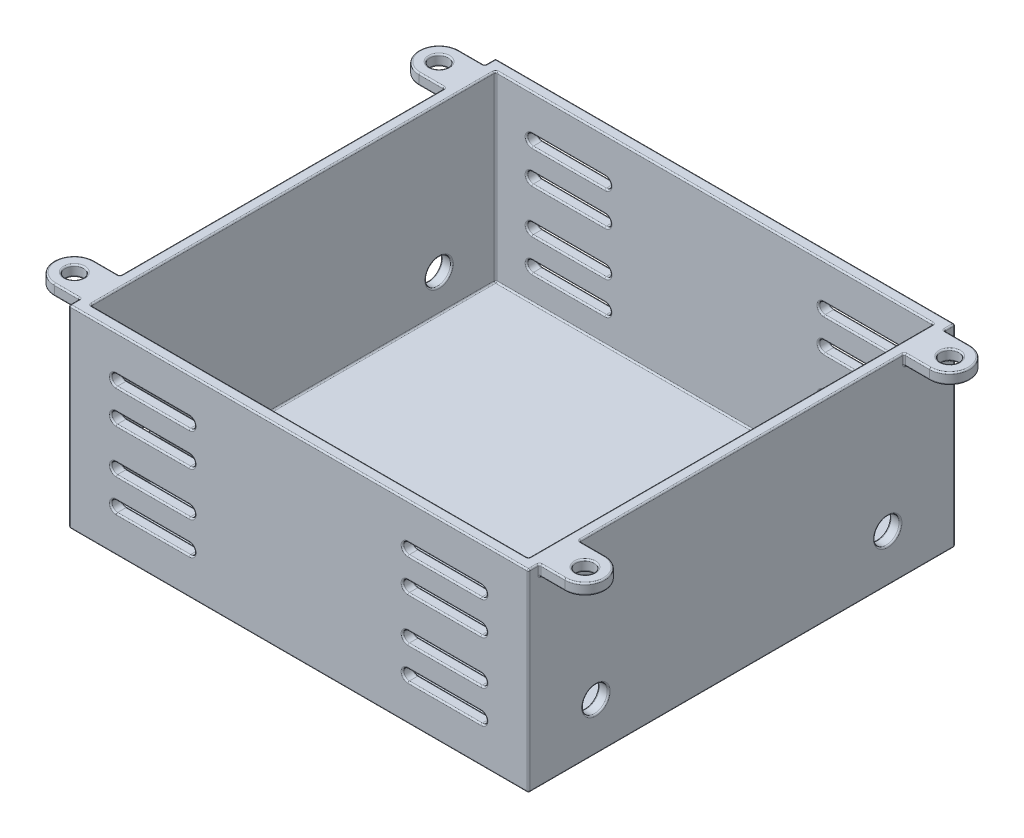
SolidWorks part; units mm, degrees
ref_plane "Front Plane" through (0, 0, 0) normal (0, 0, 1) x (1, 0, 0)
ref_plane "Top Plane" through (0, 0, 0) normal (0, 1, 0) x (1, 0, 0)
ref_plane "Right Plane" through (0, 0, 0) normal (1, 0, 0) x (0, 0, -1)
sketch "Sketch1" plane through (0, 0, 0) normal (0, 1, 0) x (1, 0, 0)
  line L0 (-35, 27.75) -> (35, 27.75) construction
  line L1 (-35, 25) -> (35, 25) construction
  line L2 (-35, 25) -> (-35, -25) construction
  line L3 (-35, -25) -> (35, -25) construction
  line L4 (35, 25) -> (35, -25) construction
  line L5 (-35, 25) -> (35, -25) construction
  line L6 (-35, -25) -> (35, 25) construction
  line L7 (-30, 27.75) -> (30, 27.75)
  line L8 (-35, -27.75) -> (35, -27.75) construction
  line L9 (30, 27.75) -> (30, -27.75)
  line L10 (30, -27.75) -> (-30, -27.75)
  line L11 (-30, -27.75) -> (-30, 27.75)
  line L12 (-35, 22.25) -> (-30, 22.25)
  line L13 (35, 22.25) -> (30, 22.25)
  line L14 (-35, -22.25) -> (-30, -22.25)
  line L15 (35, -22.25) -> (30, -22.25)
  circle A0 centre (-35, 25) radius 1.25
  circle A1 centre (-35, -25) radius 1.25
  circle A2 centre (35, -25) radius 1.25
  circle A3 centre (35, 25) radius 1.25
  circle A4 centre (-35, 25) radius 2.75
  circle A5 centre (35, 25) radius 2.75
  circle A6 centre (35, -25) radius 2.75
  circle A7 centre (-35, -25) radius 2.75
  point P0 (0, 0)
  dimension "D3" = 2.5
  dimension "D1" = 50
  dimension "D2" = 70
  dimension "D5" = 60
  dimension "D6" = 30
  dimension "D4" = 1.5
sketch "Sketch2" plane through (0, 0, 0) normal (0, 1, 0) x (1, 0, 0)
  line L0 (-30, -27.75) -> (-30, 27.75) construction
  line L1 (-30, -27.75) -> (-30, 27.75)
  line L2 (-30, 27.75) -> (30, 27.75) construction
  line L3 (-30, 27.75) -> (30, 27.75)
  line L4 (30, 27.75) -> (30, -27.75) construction
  line L5 (30, 27.75) -> (30, -27.75)
  line L6 (30, -27.75) -> (-30, -27.75) construction
  line L7 (30, -27.75) -> (-30, -27.75)
  line L8 (-31.5, -29.25) -> (-31.5, 29.25)
  line L9 (-31.5, 29.25) -> (31.5, 29.25)
  line L10 (31.5, 29.25) -> (31.5, -29.25)
  line L11 (31.5, -29.25) -> (-31.5, -29.25)
  dimension "D1" = 1.5
extrude "Boss-Extrude1" add sketch "Sketch2" against normal blind 25
sketch "Sketch3" plane through (0, -25, 0) normal (0, -1, 0) x (1, 0, 0)
  line L4 (31.5, 29.25) -> (-31.5, 29.25)
  line L5 (-31.5, 29.25) -> (-31.5, -29.25)
  line L6 (-31.5, -29.25) -> (31.5, -29.25)
  line L7 (31.5, -29.25) -> (31.5, 29.25)
  line L8 (31.5, 29.25) -> (-31.5, 29.25)
  line L9 (-31.5, 29.25) -> (-31.5, -29.25)
  line L10 (-31.5, -29.25) -> (31.5, -29.25)
  line L11 (31.5, -29.25) -> (31.5, 29.25)
  dimension "D1" = 0
extrude "Boss-Extrude2" add sketch "Sketch3" along normal blind 1.5
sketch "Sketch4" plane through (0, 0, 0) normal (0, 1, 0) x (1, 0, 0)
  line L0 (-35, 27.75) -> (35, 27.75) construction
  line L1 (-35, 27.75) -> (-30, 27.75)
  line L2 (-35, 22.25) -> (-30, 22.25) construction
  line L3 (-35, 22.25) -> (-30, 22.25)
  line L4 (35, 22.25) -> (30, 22.25) construction
  line L5 (35, 22.25) -> (30, 22.25)
  line L6 (-35, -22.25) -> (-30, -22.25) construction
  line L7 (-35, -27.75) -> (35, -27.75) construction
  line L8 (35, -22.25) -> (30, -22.25) construction
  line L9 (30, 27.75) -> (30, -27.75) construction
  line L10 (-30, -27.75) -> (-30, 27.75) construction
  line L11 (-35, -22.25) -> (-30, -22.25)
  line L12 (-35, -27.75) -> (-30, -27.75)
  line L13 (35, -22.25) -> (30, -22.25)
  line L14 (30, 27.75) -> (30, 22.25)
  line L15 (-30, -27.75) -> (-30, -22.25)
  line L16 (-30, 22.25) -> (-30, 27.75)
  line L17 (30, 27.75) -> (35, 27.75)
  line L18 (30, -22.25) -> (30, -27.75)
  line L19 (30, -27.75) -> (35, -27.75)
  circle A0 centre (-35, 25) radius 2.75 construction
  arc A1 (-35, 27.75) -> (-35, 22.25) centre (-35, 25) ccw
  circle A2 centre (-35, 25) radius 1.25 construction
  circle A3 centre (-35, 25) radius 1.25
  circle A4 centre (35, 25) radius 1.25 construction
  circle A5 centre (35, 25) radius 2.75 construction
  circle A6 centre (35, 25) radius 1.25
  arc A7 (35, 22.25) -> (35, 27.75) centre (35, 25) ccw
  circle A8 centre (-35, -25) radius 1.25 construction
  circle A9 centre (-35, -25) radius 2.75 construction
  circle A10 centre (35, -25) radius 1.25 construction
  circle A11 centre (35, -25) radius 2.75 construction
  circle A12 centre (-35, -25) radius 1.25
  arc A13 (-35, -22.25) -> (-35, -27.75) centre (-35, -25) ccw
  circle A14 centre (35, -25) radius 1.25
  arc A15 (35, -27.75) -> (35, -22.25) centre (35, -25) ccw
extrude "Boss-Extrude3" add sketch "Sketch4" against normal blind 1.5
sketch "Sketch5" plane through (0, 0, 0) normal (0, 0, 1) x (1, 0, 0)
  line L0 (-31.5, -13.25) -> (31.5, -13.25) construction
  line L1 (-31.5, -26.5) -> (-31.5, 0) construction
  line L2 (31.5, -26.5) -> (31.5, 0) construction
  line L3 (-25, -5.75) -> (-15, -5.75) construction
  line L4 (-25, -5) -> (-15, -5)
  line L5 (-25, -6.5) -> (-15, -6.5)
  line L6 (-25, -10.25) -> (-15, -10.25) construction
  line L7 (-25, -9.5) -> (-15, -9.5)
  line L8 (-25, -11) -> (-15, -11)
  line L9 (0, -13.25) -> (0, -21.5125) construction
  line L10 (-25, -16.25) -> (-15, -16.25) construction
  line L11 (-25, -17) -> (-15, -17)
  line L12 (-25, -15.5) -> (-15, -15.5)
  line L13 (-25, -20.75) -> (-15, -20.75) construction
  line L14 (-25, -21.5) -> (-15, -21.5)
  line L15 (-25, -20) -> (-15, -20)
  line L16 (25, -20.75) -> (15, -20.75) construction
  line L17 (25, -21.5) -> (15, -21.5)
  line L18 (25, -20) -> (15, -20)
  line L19 (25, -16.25) -> (15, -16.25) construction
  line L20 (25, -17) -> (15, -17)
  line L21 (25, -15.5) -> (15, -15.5)
  line L22 (25, -10.25) -> (15, -10.25) construction
  line L23 (25, -9.5) -> (15, -9.5)
  line L24 (25, -11) -> (15, -11)
  line L25 (25, -5.75) -> (15, -5.75) construction
  line L26 (25, -5) -> (15, -5)
  line L27 (25, -6.5) -> (15, -6.5)
  arc A0 (-25, -5) -> (-25, -6.5) centre (-25, -5.75) ccw
  arc A1 (-15, -6.5) -> (-15, -5) centre (-15, -5.75) ccw
  arc A2 (-25, -9.5) -> (-25, -11) centre (-25, -10.25) ccw
  arc A3 (-15, -11) -> (-15, -9.5) centre (-15, -10.25) ccw
  arc A4 (-25, -17) -> (-25, -15.5) centre (-25, -16.25) cw
  arc A5 (-15, -15.5) -> (-15, -17) centre (-15, -16.25) cw
  arc A6 (-25, -21.5) -> (-25, -20) centre (-25, -20.75) cw
  arc A7 (-15, -20) -> (-15, -21.5) centre (-15, -20.75) cw
  arc A8 (25, -21.5) -> (25, -20) centre (25, -20.75) ccw
  arc A9 (15, -20) -> (15, -21.5) centre (15, -20.75) ccw
  arc A10 (25, -17) -> (25, -15.5) centre (25, -16.25) ccw
  arc A11 (15, -15.5) -> (15, -17) centre (15, -16.25) ccw
  arc A12 (25, -9.5) -> (25, -11) centre (25, -10.25) cw
  arc A13 (15, -11) -> (15, -9.5) centre (15, -10.25) cw
  arc A14 (25, -5) -> (25, -6.5) centre (25, -5.75) cw
  arc A15 (15, -6.5) -> (15, -5) centre (15, -5.75) cw
  point P8 (-20, -5.75)
  point P16 (-20, -10.25)
  point P25 (-20, -16.25)
  point P32 (-20, -20.75)
  point P39 (20, -20.75)
  point P46 (20, -16.25)
  point P53 (20, -10.25)
  point P60 (20, -5.75)
  dimension "D1" = 10
  dimension "D2" = 1.5
  dimension "D3" = 20
  dimension "D4" = 7.5
  dimension "D5" = 4.5
extrude "Cut-Extrude1" cut sketch "Sketch5" against normal through all both and the other way through all
sketch "Sketch6" plane through (0, 0, 0) normal (1, 0, 0) x (0, 0, -1)
  line L0 (0, 0) -> (0, -20) construction
  line L1 (0, -20) -> (-20, -20) construction
  circle A0 centre (-20, -20) radius 1.75
  circle A1 centre (20, -20) radius 1.75
  dimension "D1" = 3.5
  dimension "D2" = 20
  dimension "D3" = 20
extrude "Cut-Extrude2" cut sketch "Sketch6" against normal through all both and the other way through all
fillet "Fillet1" radius 0.2 208 edges at (30, -20, -21.75) (-30, -20, -18.25) (31.5, -20, -21.75) (-31.5, -20, -18.25) (30, -20, 18.25) (-30, -20, 21.75) (31.5, -20, 18.25) (-31.5, -20, 21.75) (20, -6.5, -29.25) (14.25, -5.75, -29.25) (20, -5, -29.25) (25.75, -5.75, -29.25) (14.25, -5.75, 29.25) (20, -5, 29.25) (25.75, -5.75, 29.25) (20, -11, -29.25) (14.25, -10.25, -29.25) (20, -9.5, -29.25) (25.75, -10.25, -29.25) (20, -11, 29.25) (14.25, -10.25, 29.25) (20, -9.5, 29.25) (25.75, -10.25, 29.25) (20, -17, -29.25) (14.25, -16.25, -29.25) (20, -15.5, -29.25) (25.75, -16.25, -29.25) (20, -17, 29.25) (14.25, -16.25, 29.25) (20, -15.5, 29.25) (25.75, -16.25, 29.25) (20, -21.5, -29.25) (14.25, -20.75, -29.25) (20, -20, -29.25) (25.75, -20.75, -29.25) (20, -21.5, 29.25) (14.25, -20.75, 29.25) (20, -20, 29.25) (25.75, -20.75, 29.25) (-20, -20, -29.25) (-14.25, -20.75, -29.25) (-20, -21.5, -29.25) (-25.75, -20.75, -29.25) (-20, -20, 29.25) (-14.25, -20.75, 29.25) (-20, -21.5, 29.25) (-25.75, -20.75, 29.25) (-20, -15.5, -29.25) (-14.25, -16.25, -29.25) (-20, -17, -29.25) (-25.75, -16.25, -29.25) (-20, -15.5, 29.25) (-14.25, -16.25, 29.25) (-20, -17, 29.25) (-25.75, -16.25, 29.25) (-20, -9.5, -29.25) (-14.25, -10.25, -29.25) (-20, -11, -29.25) (-25.75, -10.25, -29.25) (-20, -9.5, 29.25) (-14.25, -10.25, 29.25) (-20, -11, 29.25) (-25.75, -10.25, 29.25) (-25.75, -5.75, 29.25) (-20, -6.5, 29.25) (-14.25, -5.75, 29.25) (-20, -5, 29.25) (-25.75, -5.75, -29.25) (-20, -6.5, -29.25) (-14.25, -5.75, -29.25) (-20, -5, -29.25) (-20, -6.5, 27.75) (-14.25, -5.75, 27.75) (-20, -5, 27.75) (-25.75, -5.75, 27.75) (20, -5, 27.75) (14.25, -5.75, 27.75) (20, -6.5, 27.75) (25.75, -5.75, 27.75) (20, -9.5, 27.75) (14.25, -10.25, 27.75) (20, -11, 27.75) (25.75, -10.25, 27.75) (20, -15.5, 27.75) (14.25, -16.25, 27.75) (20, -17, 27.75) (25.75, -16.25, 27.75) (20, -20, 27.75) (14.25, -20.75, 27.75) (20, -21.5, 27.75) (25.75, -20.75, 27.75) (-20, -21.5, 27.75) (-14.25, -20.75, 27.75) (-20, -20, 27.75) (-25.75, -20.75, 27.75) (-20, -17, 27.75) (-14.25, -16.25, 27.75) (-20, -15.5, 27.75) (-25.75, -16.25, 27.75) (-20, -11, 27.75) (-14.25, -10.25, 27.75) (-20, -9.5, 27.75) (-25.75, -10.25, 27.75) (33.25, -1.5, 27.75) (33.25, -1.5, 22.25) (37.75, -1.5, 25) (33.25, 0, 27.75) (33.25, 0, 22.25) (37.75, 0, 25) (35, -1.5, 26.25) (35, 0, 26.25) (31.5, -1.5, 25) (31.5, -0.75, 22.25) (31.5, -0.75, 27.75) (-33.25, -1.5, 22.25) (-33.25, -1.5, 27.75) (-37.75, -1.5, 25) (-33.25, 0, 22.25) (-33.25, 0, 27.75) (-37.75, 0, 25) (-35, -1.5, 26.25) (-35, 0, 26.25) (-31.5, -1.5, 25) (-31.5, -0.75, 27.75) (-31.5, -0.75, 22.25) (33.25, -1.5, -22.25) (33.25, -1.5, -27.75) (37.75, -1.5, -25) (33.25, 0, -22.25) (33.25, 0, -27.75) (37.75, 0, -25) (35, -1.5, -23.75) (35, 0, -23.75) (31.5, -1.5, -25) (31.5, -0.75, -27.75) (31.5, -0.75, -22.25) (-35, -1.5, -23.75) (-35, 0, -23.75) (-37.75, 0, -25) (-37.75, -1.5, -25) (-33.25, -1.5, -22.25) (-33.25, 0, -22.25) (-33.25, 0, -27.75) (-33.25, -1.5, -27.75) (-31.5, -1.5, -25) (-31.5, -0.75, -22.25) (-31.5, -0.75, -27.75) (31.5, -26.5, 0) (0, -26.5, 29.25) (-31.5, -26.5, 0) (0, -26.5, -29.25) (0, 0, 27.75) (0, -25, 27.75) (30, 0, 0) (30, -25, 0) (0, 0, -27.75) (0, -25, -27.75) (-30, 0, 0) (-30, -25, 0) (30, -12.5, 27.75) (30, -12.5, -27.75) (-30, -12.5, -27.75) (-30, -12.5, 27.75) (0, 0, 29.25) (31.5, 0, -28.5) (31.5, 0, 0) (31.5, 0, 28.5) (0, 0, -29.25) (-31.5, 0, 28.5) (-31.5, 0, 0) (-31.5, 0, -28.5) (31.5, -13.25, 29.25) (31.5, -13.25, -29.25) (-31.5, -13.25, -29.25) (-31.5, -13.25, 29.25) (-20, -6.5, -27.75) (-14.25, -5.75, -27.75) (-20, -5, -27.75) (-25.75, -5.75, -27.75) (20, -5, -27.75) (14.25, -5.75, -27.75) (20, -6.5, -27.75) (25.75, -5.75, -27.75) (20, -9.5, -27.75) (14.25, -10.25, -27.75) (20, -11, -27.75) (25.75, -10.25, -27.75) (20, -15.5, -27.75) (14.25, -16.25, -27.75) (20, -17, -27.75) (25.75, -16.25, -27.75) (20, -20, -27.75) (14.25, -20.75, -27.75) (20, -21.5, -27.75) (25.75, -20.75, -27.75) (-20, -21.5, -27.75) (-14.25, -20.75, -27.75) (-20, -20, -27.75) (-25.75, -20.75, -27.75) (-20, -17, -27.75) (-14.25, -16.25, -27.75) (-20, -15.5, -27.75) (-25.75, -16.25, -27.75) (-20, -11, -27.75) (-14.25, -10.25, -27.75) (-20, -9.5, -27.75) (-25.75, -10.25, -27.75) (20, -6.5, 29.25)
